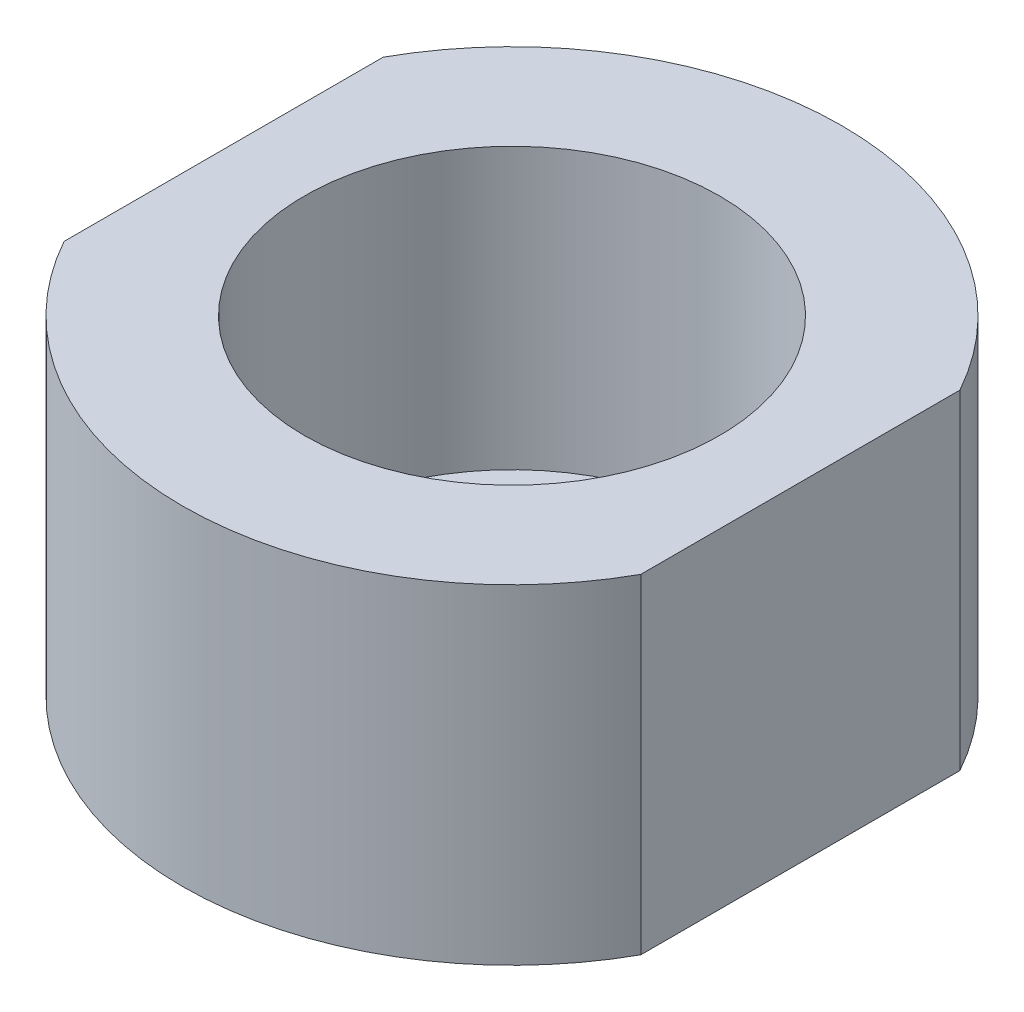
SolidWorks part; units mm, degrees
ref_plane "Front Plane" through (0, 0, 0) normal (0, 0, 1) x (1, 0, 0)
ref_plane "Top Plane" through (0, 0, 0) normal (0, 1, 0) x (1, 0, 0)
ref_plane "Right Plane" through (0, 0, 0) normal (1, 0, 0) x (0, 0, -1)
sketch "Sketch1" plane through (0, 0, 0) normal (0, 1, 0) x (1, 0, 0)
  circle A0 centre (0, 0) radius 25.4
  dimension "D1" = 50.8
extrude "Boss-Extrude1" add sketch "Sketch1" along normal blind 25.4
sketch "Sketch2" plane through (0, 25.4, 0) normal (0, 1, 0) x (1, 0, 0)
  circle A0 centre (0, 0) radius 16
  dimension "D1" = 32
extrude "Cut-Extrude1" cut sketch "Sketch2" against normal offset from surface (21.59 mm away) 3.81 up to face at (0, 0, 25.4)
sketch "Sketch3" plane through (0, 0, 0) normal (0, 0, 1) x (1, 0, 0)
  line L1 (25.4, 25.4) -> (22.225, 25.4)
  line L2 (25.4, 25.4) -> (25.4, 8.89)
  line L3 (25.4, 8.89) -> (22.225, 8.89)
  line L4 (22.225, 25.4) -> (22.225, 8.89)
  line L5 (25.4, 25.4) -> (22.225, 8.89) construction
  line L6 (25.4, 8.89) -> (22.225, 25.4) construction
  line L7 (-25.4, 25.4) -> (-22.225, 25.4)
  line L8 (-25.4, 25.4) -> (-25.4, 8.89)
  line L9 (-25.4, 8.89) -> (-22.225, 8.89)
  line L10 (-22.225, 25.4) -> (-22.225, 8.89)
  line L11 (-25.4, 25.4) -> (-22.225, 8.89) construction
  line L12 (-25.4, 8.89) -> (-22.225, 25.4) construction
  point P4 (23.8125, 17.145)
  point P10 (-23.8125, 17.145)
  dimension "D1" = 16.51
  dimension "D2" = 44.45
extrude "Cut-Extrude2" cut sketch "Sketch3" against normal up to next and the other way up to next
sketch "Sketch4" plane through (0, 3.81, 0) normal (0, 1, 0) x (1, 0, 0)
  line L0 (0, 0) -> (0, 8.89) construction
  circle A0 centre (0, 8.89) radius 1
  circle A1 centre (7.699, -4.445) radius 1
  circle A2 centre (-7.699, -4.445) radius 1
  point P11 (0, 0)
  dimension "D1" = 2
  dimension "D2" = 8.89
  dimension "D3" = 3
extrude "Cut-Extrude3" cut sketch "Sketch4" against normal up to next
sketch "Sketch5" plane through (0, 8.89, 0) normal (0, 1, 0) x (1, 0, 0)
  line L1 (22.225, 12.2967) -> (22.225, -12.2967)
  line L2 (22.225, 12.2967) -> (22.225, -12.2967)
  line L3 (-22.225, -12.2967) -> (-22.225, 12.2967)
  line L4 (-22.225, -12.2967) -> (-22.225, 12.2967)
  arc A1 (22.225, -12.2967) -> (22.225, 12.2967) centre (0, 0) ccw
  arc A2 (22.225, -12.2967) -> (22.225, 12.2967) centre (0, 0) ccw
  arc A3 (-22.225, 12.2967) -> (-22.225, -12.2967) centre (0, 0) ccw
  arc A4 (-22.225, 12.2967) -> (-22.225, -12.2967) centre (0, 0) ccw
  dimension "D1" = 0
  dimension "D2" = 0
extrude "Cut-Extrude4" cut sketch "Sketch5" against normal up to next
